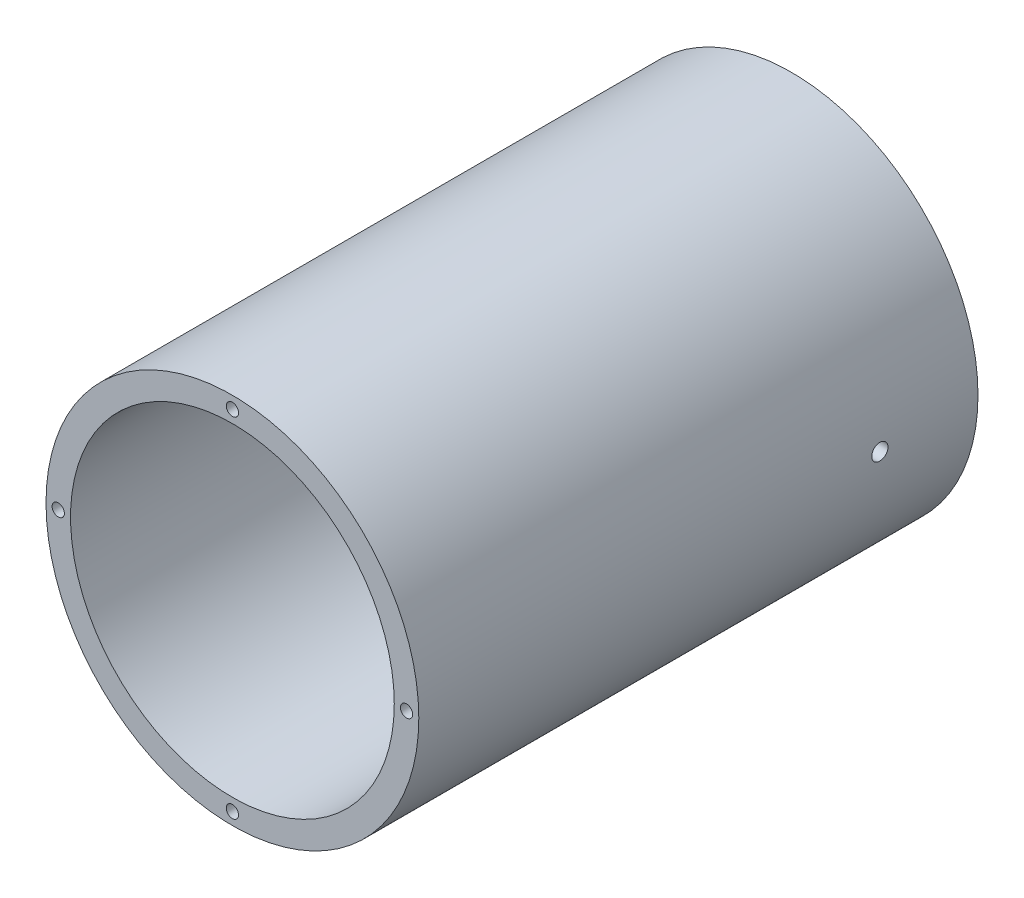
SolidWorks part; units mm, degrees
material "AISI 1020 钢，冷轧"
ref_plane "前视基准面" through (0, 0, 0) normal (0, 0, 1) x (1, 0, 0)
ref_plane "上视基准面" through (0, 0, 0) normal (0, 1, 0) x (1, 0, 0)
ref_plane "右视基准面" through (0, 0, 0) normal (1, 0, 0) x (0, 0, -1)
sketch "草图1" plane through (0, 0, 0) normal (0, 0, 1) x (1, 0, 0)
  circle A0 centre (0, 0) radius 38
  circle A1 centre (0, 0) radius 33
  dimension "D1" = 76
  dimension "D2" = 66
extrude "凸台-拉伸1" add sketch "草图1" along normal mid plane 114
hole_wizard "M3 螺纹孔1" positions "草图3" profile "草图2" tap size "M3" standard "GB"
sketch "草图3" plane through (0, 0, 57) normal (0, 0, 1) x (1, 0, 0)
  point P0 (0, 35.5)
  point P10 (35.5, 0)
  point P11 (0, -35.5)
  point P12 (-35.5, 0)
  dimension "D1" = 35.5
  dimension "D2" = 4
sketch "草图2" plane through (0, 35.5, 57) normal (1, 0, 0) x (0, -1, 0)
  line L0 (0, 0) -> (0, 9.2511)
  line L1 (0, 9.2511) -> (1.25, 8.5)
  line L2 (1.25, 8.5) -> (1.25, 0)
  line L5 (1.25, 0) -> (0, 0)
  line L10 (0, 9.2511) -> (-1.25, 8.5) construction
  line L11 (0, -6.35) -> (0, 107.95) construction
  dimension "螺纹孔钻头直径" = 2.5
  dimension "螺纹孔钻头深度" = 8.5
  dimension "导头角度" = 118
cosmetic thread "孔螺蚊线3" parameters "D1"=6, "D2"=3
cosmetic thread "孔螺蚊线4" parameters "D1"=6, "D2"=3
cosmetic thread "孔螺蚊线5" parameters "D1"=6, "D2"=3
cosmetic thread "孔螺蚊线6" parameters "D1"=6, "D2"=3
sketch "草图5" plane through (0, 0, -57) normal (0, 0, -1) x (-1, 0, 0)
  circle A0 centre (0, 0) radius 38
  circle A1 centre (0, 0) radius 14
  circle A2 centre (0, 0) radius 38 construction
  dimension "D1" = 28
extrude "凸台-拉伸2" [suppressed] add sketch "草图5" along normal blind 10
hole_wizard "M3 螺纹孔3" positions "草图11" profile "草图13" tap size "M3" standard "GB"
sketch "草图11" plane through (13.8063, 28.9872, -57) normal (0, 0, -1) x (-1, 0, 0)
  line L0 (13.8063, -28.9872) -> (13.8063, -2.0872) construction
  line L3 (13.8063, -28.9872) -> (49.3063, -28.9872) construction
  circle A0 centre (13.8063, -28.9872) radius 35.5
  point P0 (49.3063, -28.9872)
  point P10 (13.8063, -64.4872)
  point P11 (-21.6937, -28.9872)
  point P12 (13.8063, 6.5128)
  dimension "D1" = 71
  dimension "D3" = 90
  dimension "D2" = 4
sketch "草图13" plane through (-35.5, 0, -57) normal (1, 0, 0) x (0, 1, 0)
  line L0 (0, 0) -> (0, 9.2511)
  line L1 (0, 9.2511) -> (1.25, 8.5)
  line L2 (1.25, 8.5) -> (1.25, 0)
  line L5 (1.25, 0) -> (0, 0)
  line L10 (0, 9.2511) -> (-1.25, 8.5) construction
  line L11 (0, -6.35) -> (0, 107.95) construction
  dimension "螺纹孔钻头直径" = 2.5
  dimension "螺纹孔钻头深度" = 8.5
  dimension "导头角度" = 118
cosmetic thread "孔螺蚊线13" parameters "D1"=6, "D2"=3
cosmetic thread "孔螺蚊线15" parameters "D1"=6, "D2"=3
cosmetic thread "孔螺蚊线16" parameters "D1"=6, "D2"=3
cosmetic thread "孔螺蚊线17" parameters "D1"=6, "D2"=3
hole_wizard "M4 螺纹孔1" positions "3D草图1" profile "草图14" tap size "M4" standard "GB" end condition up to next
sketch3d "3D草图1"
  line L0 (-38, 0, -37) -> (38, 0, -37) construction
  line L2 (0, 0, 0) -> (0, 0, -37) construction
  circle A0 centre (0, 0, -57) radius 38 construction
  point P0 (38, 0, -37)
  point P2 (-38, 0, -37)
  point P15 (0, 0, -19)
  dimension "D1" = 20
sketch "草图14" plane through (38, 0, -37) normal (0, 1, 0) x (0, 0, -1)
  line L0 (0, 0) -> (0, 5)
  line L1 (0, 5) -> (1.65, 5)
  line L2 (1.65, 5) -> (1.65, 0)
  line L5 (1.65, 0) -> (0, 0)
  line L11 (0, -6.35) -> (0, 107.95) construction
  dimension "通孔螺纹孔钻头直径" = 3.3
  dimension "通孔螺纹孔钻头深度" = 5
cosmetic thread "孔螺蚊线18" parameters "D2"=4
cosmetic thread "孔螺蚊线19" parameters "D2"=4
